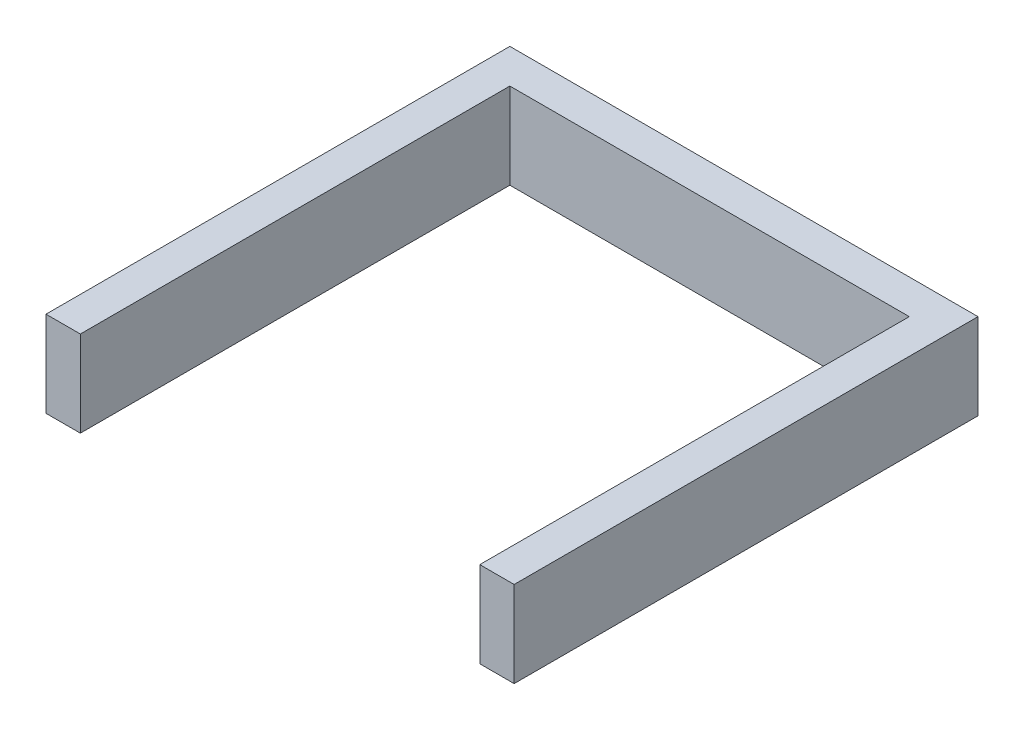
SolidWorks part; units mm, degrees
ref_plane "Front Plane" through (0, 0, 0) normal (0, 0, 1) x (1, 0, 0)
ref_plane "Top Plane" through (0, 0, 0) normal (0, 1, 0) x (1, 0, 0)
ref_plane "Right Plane" through (0, 0, 0) normal (1, 0, 0) x (0, 0, -1)
sketch "Sketch2" plane through (0, 0, 0) normal (0, 1, 0) x (1, 0, 0)
  line L0 (-2, 0) -> (-2, 27)
  line L2 (0, 0) -> (0, 25)
  line L3 (0, 25) -> (23.25, 25)
  line L4 (23.25, 0) -> (23.25, 25)
  line L5 (-2, 27) -> (25.25, 27)
  line L6 (25.25, 0) -> (25.25, 27)
  line L7 (-2, 0) -> (0, 0)
  line L8 (23.25, 0) -> (25.25, 0)
  dimension "D2" = 23.25
  dimension "D3" = 25
  dimension "D1" = 2
extrude "Boss-Extrude1" add sketch "Sketch2" along normal blind 5
